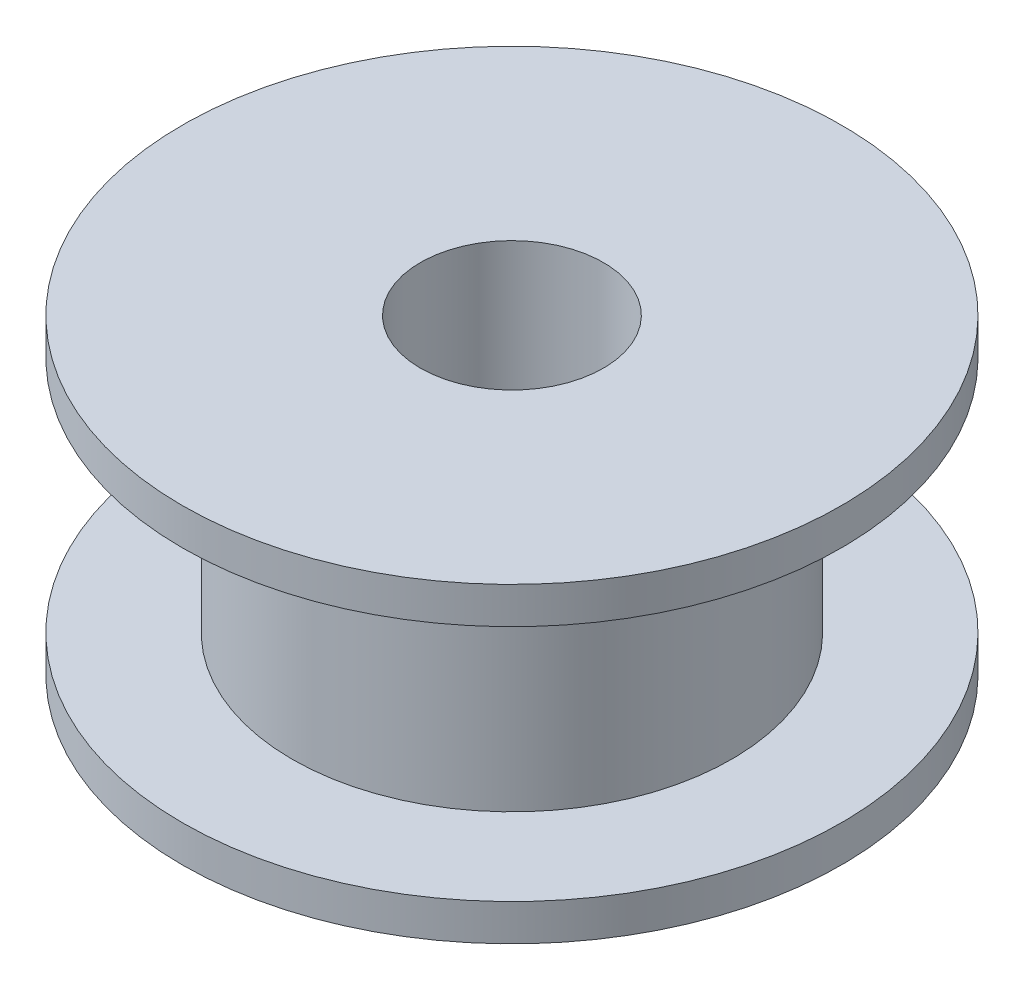
SolidWorks part; units mm, degrees
material "6061-T6 (SS)"
ref_plane "Front Plane" through (0, 0, 0) normal (0, 0, 1) x (1, 0, 0)
ref_plane "Top Plane" through (0, 0, 0) normal (0, 1, 0) x (1, 0, 0)
ref_plane "Right Plane" through (0, 0, 0) normal (1, 0, 0) x (0, 0, -1)
ref_axis "Axis1" through (0, 55, 0) along (0, -1, 0)
sketch "Sketch2" plane through (0, 0, 0) normal (0, 0, 1) x (1, 0, 0)
  line L0 (2.5, -4.25) -> (2.5, 4.25)
  line L1 (2.5, 4.25) -> (9, 4.25)
  line L2 (9, 4.25) -> (9, 3.25)
  line L3 (9, 3.25) -> (6, 3.25)
  line L4 (6, 3.25) -> (6, -3.25)
  line L5 (6, -3.25) -> (9, -3.25)
  line L6 (9, -3.25) -> (9, -4.25)
  line L7 (9, -4.25) -> (2.5, -4.25)
  line L8 (0, 0) -> (2.5, 0) construction
  line L9 (0, 55) -> (0, -55) construction
  point P3 (2.5, 0)
  point P12 (0, 0)
  dimension "D1" = 2.5
  dimension "D2" = 1
  dimension "D3" = 6.5
  dimension "D4" = 6
  dimension "D5" = 9
revolve "Revolve1" add sketch "Sketch2" angle 360 about axis through (0, 55, 0) along (0, -1, 0)
